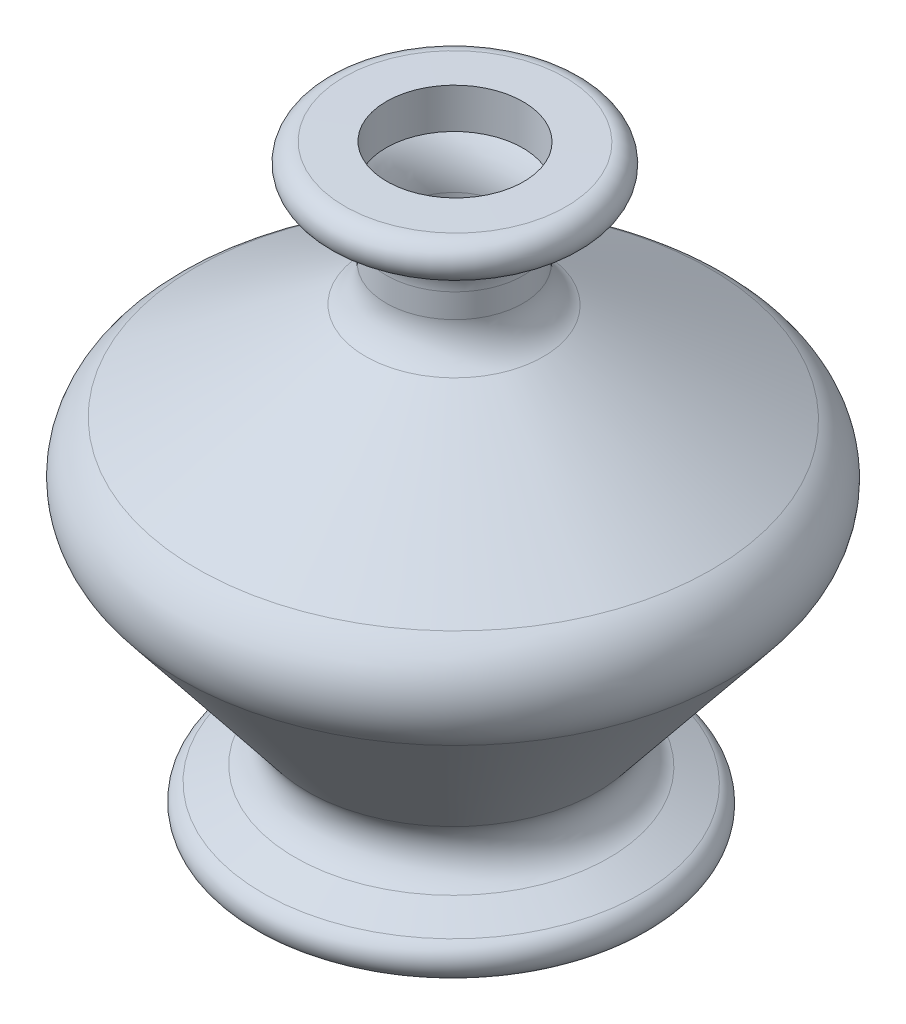
SolidWorks part; units mm, degrees
ref_plane "Front Plane" through (0, 0, 0) normal (0, 0, 1) x (1, 0, 0)
ref_plane "Top Plane" through (0, 0, 0) normal (0, 1, 0) x (1, 0, 0)
ref_plane "Right Plane" through (0, 0, 0) normal (1, 0, 0) x (0, 0, -1)
sketch "Sketch1" plane through (0, 0, 0) normal (0, 0, 1) x (1, 0, 0)
  line L0 (-18.7057, 34.9024) -> (-18.7503, 28.378)
  line L1 (-50.25, -98.6303) -> (-1.0616, -98.6303)
  line L2 (-18.555, 56.9697) -> (-18.6294, 46.0807)
  line L3 (-30, 56.9697) -> (-18.555, 56.9697)
  line L4 (-18.6233, 46.9697) -> (-18.555, 46.9697)
  line L6 (-35, 56.9697) -> (-18.555, 56.9697) construction
  line L7 (-1.0616, -98.6303) -> (-1.0916, -103.0303)
  line L8 (-18.6233, 46.9697) -> (-18.555, 46.9697)
  line L9 (-50.25, -103.0303) -> (-1.0916, -103.0303)
  line L12 (-41.7537, -93.5512) -> (-50.4961, -97.4831)
  line L13 (-24.375, 18.712) -> (-70.25, -7.7739)
  line L14 (-35, 46.9697) -> (-18.555, 46.9697) construction
  line L15 (-74.8468, -31.4955) -> (-40.1643, -75.7812)
  line L16 (-30.2403, 46.9697) -> (-30, 46.9697)
  line L17 (-71.3826, -28.7826) -> (-36.7002, -73.0682)
  line L18 (-22.175, 14.9015) -> (-68.05, -11.5844)
  line L19 (-14.3058, 34.8723) -> (-14.3504, 28.348)
  line L20 (-43.5584, -89.5384) -> (-52.3009, -93.4703)
  line L21 (-50.25, -98.6303) -> (-19.6475, -98.6303) construction
  line L22 (-50.25, -103.0303) -> (-19.6475, -103.0303) construction
  arc A0 (-30, 56.9697) -> (-30, 46.9697) centre (-30, 51.9697) ccw
  arc A5 (-52.3009, -93.4703) -> (-50.25, -103.0303) centre (-50.25, -98.0303) ccw
  arc A6 (-70.25, -7.7739) -> (-74.8468, -31.4955) centre (-62.25, -21.6303) ccw
  arc A7 (-18.7057, 34.9024) -> (-30.2075, 46.974) centre (-30.7054, 34.9843) ccw
  arc A8 (-24.375, 18.712) -> (-18.7503, 28.378) centre (-30, 28.4548) ccw
  arc A9 (-43.5584, -89.5384) -> (-40.1643, -75.7812) centre (-47.25, -81.3303) ccw
  arc A10 (-50.4961, -97.4831) -> (-50.25, -98.6303) centre (-50.25, -98.0303) ccw
  arc A11 (-41.7537, -93.5512) -> (-36.7002, -73.0682) centre (-47.25, -81.3303) ccw
  arc A12 (-68.05, -11.5844) -> (-71.3826, -28.7826) centre (-62.25, -21.6303) ccw
  arc A13 (-22.175, 14.9015) -> (-14.3504, 28.348) centre (-30, 28.4548) ccw
  arc A14 (-14.3058, 34.8723) -> (-18.6294, 46.0807) centre (-30.7054, 34.9843) ccw
  arc A16 (-14.3058, 34.8723) -> (-30.0249, 51.3702) centre (-30.7054, 34.9843) ccw construction
  point P4 (278.4396, -85.2999)
  point P6 (144.4272, -67.5449)
  point P10 (249.5218, 85.3515)
  point P13 (252.6064, -21.6303)
  point P21 (278.4396, -85.2999)
  point P22 (249.5218, 85.3515)
  point P24 (252.6064, -21.6303)
  point P51 (-18.5922, 51.5252)
  dimension "D4" = 4.2864
  dimension "D9" = 1.0616
  dimension "D12" = 10
  dimension "D14" = 32
  dimension "D10" = 1.0916
  dimension "D6" = 12
  dimension "D7" = 11.25
  dimension "D8" = 9
  dimension "D11" = 14.3058
  dimension "D5" = 14.3504
  dimension "D13" = 22.175
  dimension "D15" = 30.2403
  dimension "D16" = 36.7002
  dimension "D17" = 40.1643
  dimension "D18" = 41.7537
  dimension "D19" = 50.25
  dimension "D20" = 14.9015
  dimension "D21" = 18.555
  dimension "D22" = 62.25
  dimension "D2" = 4.4
  dimension "D3" = 10
revolve "Revolve1" add sketch "Sketch1" angle 360 about L7
